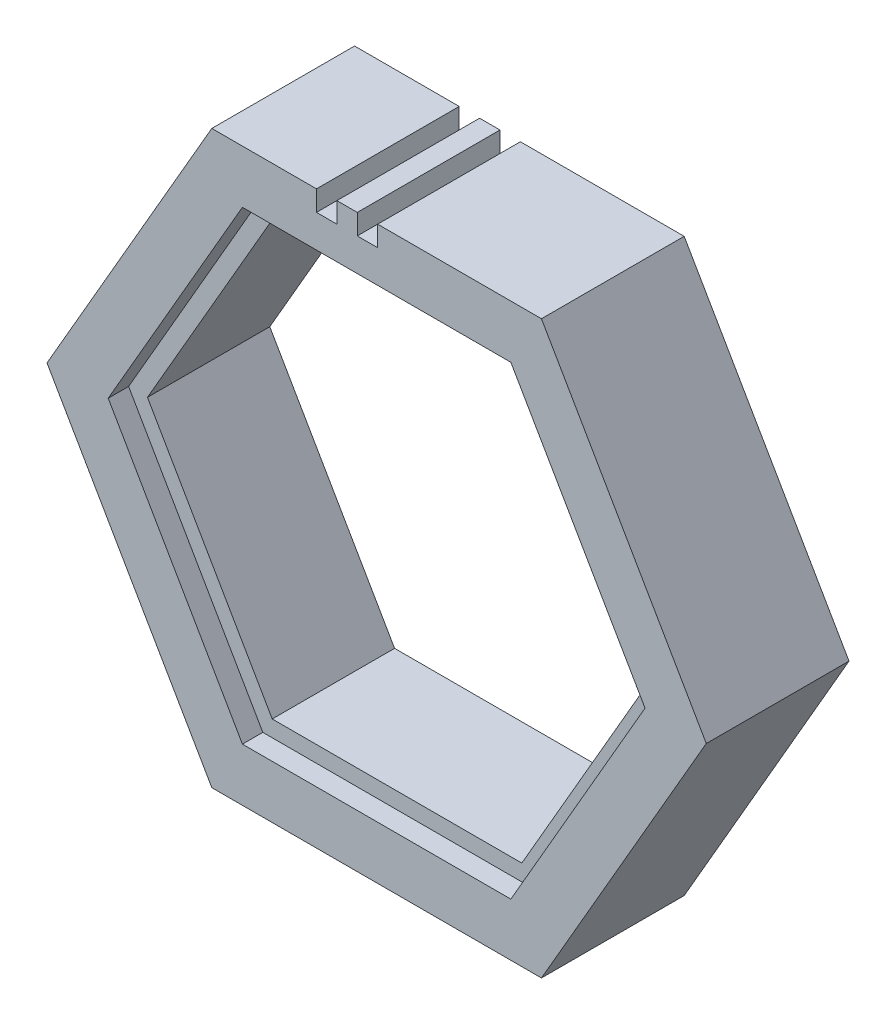
SolidWorks part; units mm, degrees
ref_plane "Front" through (0, 0, 0) normal (0, 0, 1) x (1, 0, 0)
ref_plane "Top" through (0, 0, 0) normal (0, 1, 0) x (1, 0, 0)
ref_plane "Right" through (0, 0, 0) normal (1, 0, 0) x (0, 0, -1)
sketch "Sketch1" plane through (0, 0, 0) normal (0, 0, 1) x (1, 0, 0)
  line L1 (6.5818, 0) -> (3.2909, 5.7)
  line L2 (3.2909, 5.7) -> (-3.2909, 5.7)
  line L3 (-3.2909, 5.7) -> (-6.5818, 0)
  line L4 (-6.5818, 0) -> (-3.2909, -5.7)
  line L5 (-3.2909, -5.7) -> (3.2909, -5.7)
  line L6 (3.2909, -5.7) -> (6.5818, 0)
  line L7 (8.0829, 0) -> (4.0415, 7)
  line L8 (4.0415, 7) -> (-4.0415, 7)
  line L9 (-4.0415, 7) -> (-8.0829, 0)
  line L10 (-8.0829, 0) -> (-4.0415, -7)
  line L11 (-4.0415, -7) -> (4.0415, -7)
  line L12 (4.0415, -7) -> (8.0829, 0)
  circle A0 centre (0, 0) radius 5.7 construction
  circle A1 centre (0, 0) radius 7 construction
extrude "Boss-Extrude1" add sketch "Sketch1" along normal blind 1 and the other way blind 2.5
sketch "Sketch3" plane through (0, 0, 0) normal (0, 0, 1) x (1, 0, 0)
  line L0 (-6.5818, 0) -> (-3.2909, -5.7) construction
  line L7 (6.1199, 0) -> (3.06, 5.3)
  line L8 (3.06, 5.3) -> (-3.06, 5.3)
  line L9 (-3.06, 5.3) -> (-6.1199, 0)
  line L10 (-6.1199, 0) -> (-3.06, -5.3)
  line L11 (-3.06, -5.3) -> (3.06, -5.3)
  line L12 (3.06, -5.3) -> (6.1199, 0)
  line L13 (6.5818, 0) -> (3.2909, 5.7)
  line L14 (3.2909, 5.7) -> (-3.2909, 5.7)
  line L15 (-3.2909, 5.7) -> (-6.5818, 0)
  line L16 (-6.5818, 0) -> (-3.2909, -5.7)
  line L17 (-3.2909, -5.7) -> (3.2909, -5.7)
  line L18 (3.2909, -5.7) -> (6.5818, 0)
  circle A0 centre (0, 0) radius 5.3 construction
  circle A1 centre (0, 0) radius 5.7 construction
extrude "Boss-Extrude2" add sketch "Sketch3" against normal up to surface (2.5 mm away) and the other way blind 0.5 up to face at (0, 0, -2.5)
sketch "Sketch4" plane through (0, 0, 1) normal (0, 0, 1) x (1, 0, 0)
  line L0 (4.0415, 7) -> (-4.0415, 7) construction
  line L1 (-1.4748, 7) -> (-0.9748, 7)
  line L2 (-1.4748, 7) -> (-1.4748, 6.5)
  line L3 (-1.4748, 6.5) -> (-0.9748, 6.5)
  line L4 (-0.9748, 7) -> (-0.9748, 6.5)
  line L5 (-0.4748, 7) -> (0.0252, 7)
  line L6 (-0.4748, 7) -> (-0.4748, 6.5)
  line L7 (-0.4748, 6.5) -> (0.0252, 6.5)
  line L8 (0.0252, 7) -> (0.0252, 6.5)
  dimension "D1" = 0.5
  dimension "D2" = 0.5
  dimension "D3" = 2
extrude "Cut-Extrude1" cut sketch "Sketch4" against normal through all
